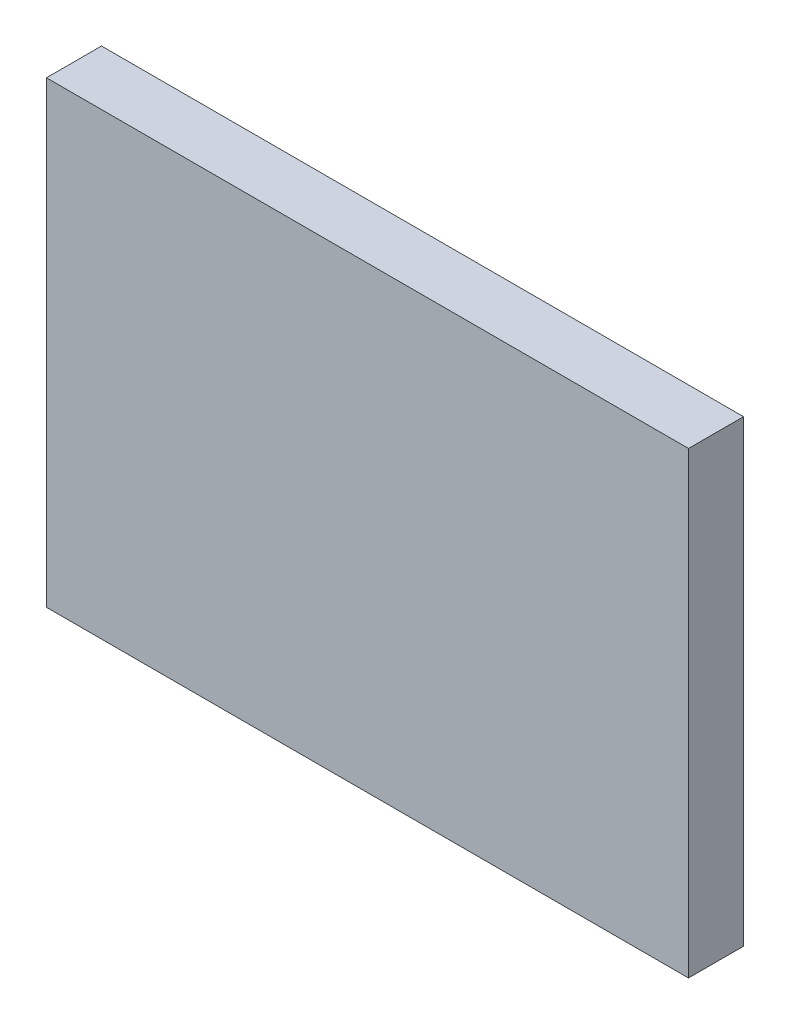
SolidWorks part; units mm, degrees
material "Silicon Dioxide"
ref_plane "Front Plane" through (0, 0, 0) normal (0, 0, 1) x (1, 0, 0)
ref_plane "Top Plane" through (0, 0, 0) normal (0, 1, 0) x (1, 0, 0)
ref_plane "Right Plane" through (0, 0, 0) normal (1, 0, 0) x (0, 0, -1)
sketch "Sketch1" plane through (0, 0, 0) normal (0, 0, 1) x (1, 0, 0)
  line L1 (-17.5, 12.5) -> (17.5, 12.5)
  line L2 (-17.5, 12.5) -> (-17.5, -12.5)
  line L3 (-17.5, -12.5) -> (17.5, -12.5)
  line L4 (17.5, 12.5) -> (17.5, -12.5)
  line L5 (-17.5, 12.5) -> (17.5, -12.5) construction
  line L6 (-17.5, -12.5) -> (17.5, 12.5) construction
  point P0 (0, 0)
  point P5 (0, 0)
  dimension "D1" = 25
  dimension "D2" = 35
extrude "Mirror" add sketch "Sketch1" along normal blind 3
